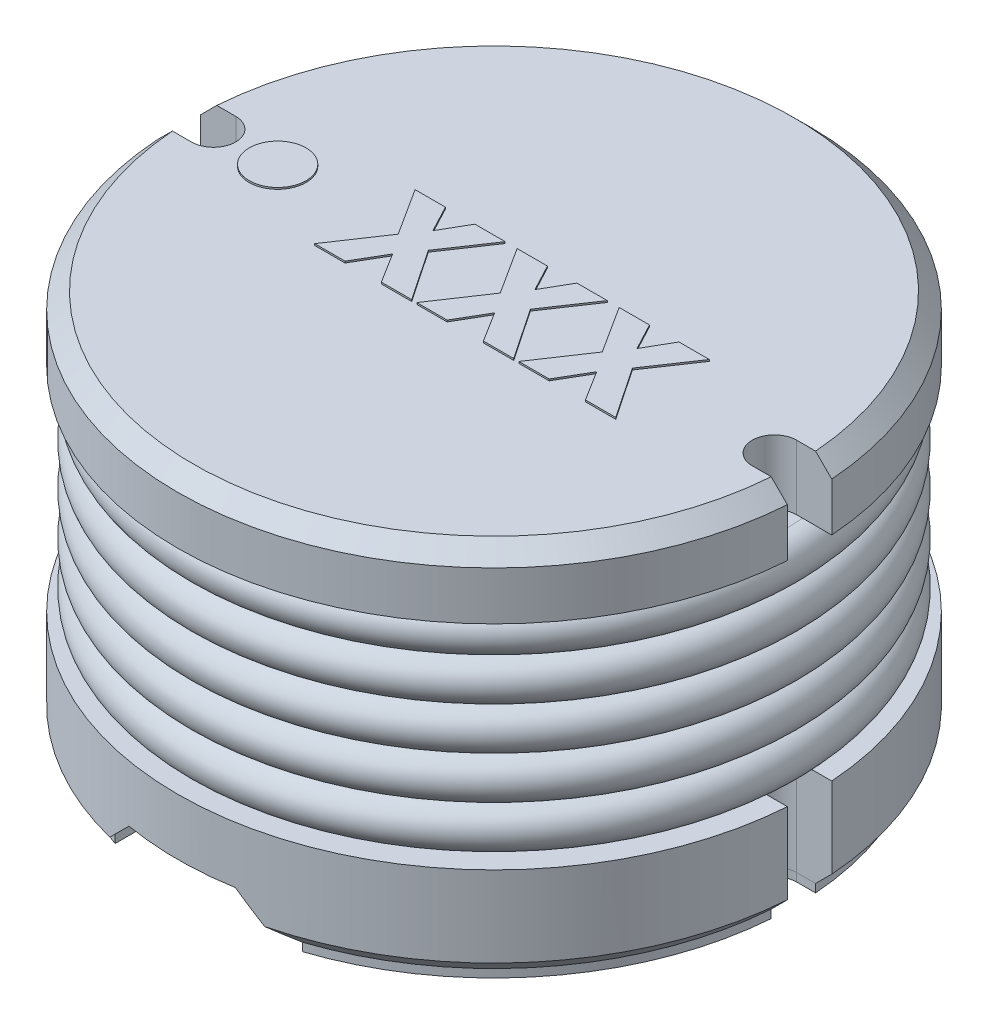
SolidWorks part; units mm, degrees
ref_plane "Front" through (0, 0, 0) normal (0, 0, 1) x (1, 0, 0)
ref_plane "Top" through (0, 0, 0) normal (0, 1, 0) x (1, 0, 0)
ref_plane "Right" through (0, 0, 0) normal (1, 0, 0) x (0, 0, -1)
sketch "Sketch1" plane through (0, 0, 0) normal (0, 0, 1) x (1, 0, 0)
  line L0 (0, -9.0753) -> (0, 11.2417) construction
  line L1 (0, 0) -> (4.65, 0)
  line L2 (4.9, 0.25) -> (4.9, 1.5)
  line L3 (4.9, 1.5) -> (4, 1.5)
  line L4 (4, 1.5) -> (4, 4.8)
  line L5 (4, 4.8) -> (4.9, 4.8)
  line L6 (4.9, 4.8) -> (4.9, 5.55)
  line L7 (4.65, 5.8) -> (0, 5.8)
  line L8 (0, 5.8) -> (0, 0)
  line L9 (4.9, 5.55) -> (4.65, 5.8)
  line L10 (4.65, 0) -> (4.9, 0.25)
  point P4 (4.9, 0)
  point P10 (4.9, 5.8)
  dimension "D1" = 9.8
  dimension "D2" = 5.8
  dimension "D3" = 1
  dimension "D4" = 1.5
  dimension "D5" = 8
revolve "Revolve: Main Core Shape" add sketch "Sketch1" angle 360 about L0
sketch "Sketch2" plane through (0, 0, 0) normal (0, 0, 1) x (1, 0, 0)
  line L0 (-1.45, 0) -> (-0.825, 0.625)
  line L1 (-4.65, 0) -> (4.65, 0) construction
  line L2 (-0.825, 0.625) -> (0.825, 0.625)
  line L3 (0.825, 0.625) -> (1.45, 0)
  line L4 (1.45, 0) -> (-1.45, 0)
  line L5 (0, -1.0768) -> (0, 6.9039) construction
  dimension "D1" = 45
  dimension "D2" = 2.9
  dimension "D3" = 0.625
extrude "CutExtd: Bottom Notch" cut sketch "Sketch2" against normal through all and the other way through all
sketch "Sketch3" plane through (0, 0, 0) normal (0, 1, 0) x (1, 0, 0)
  line L0 (-4.9, 0) -> (4.9, 0) construction
  line L1 (-5.4563, 0) -> (-4.3437, 0) construction
  line L2 (-5.4563, 0.3437) -> (-4.3437, 0.3437)
  line L3 (-5.4563, -0.3437) -> (-4.3437, -0.3437)
  line L4 (5.4563, 0) -> (4.3437, 0) construction
  line L5 (5.4563, -0.3437) -> (4.3437, -0.3437)
  line L6 (5.4563, 0.3437) -> (4.3437, 0.3437)
  circle A0 centre (0, 0) radius 4.9 construction
  arc A1 (-5.4563, 0.3437) -> (-5.4563, -0.3437) centre (-5.4563, 0) ccw
  arc A2 (-4.3437, -0.3437) -> (-4.3437, 0.3437) centre (-4.3437, 0) ccw
  arc A3 (5.4563, -0.3437) -> (5.4563, 0.3437) centre (5.4563, 0) ccw
  arc A4 (4.3437, 0.3437) -> (4.3437, -0.3437) centre (4.3437, 0) ccw
  circle A5 centre (0, 0) radius 4.3437 construction
  circle A8 centre (0, 0) radius 4 construction
  circle A9 centre (0, 0) radius 4 construction
  point P7 (-4.9, 0)
  point P13 (4.9, 0)
extrude "CutExtd: Top/Bot Wire PassThrus" cut sketch "Sketch3" along normal through all
sketch "Sketch4" plane through (0, 0, 0) normal (0, 1, 0) x (1, 0, 0)
  line L1 (-1.45, -4.4181) -> (-1.45, 4.4181)
  line L2 (-4.6373, 0.3437) -> (-4.3437, 0.3437)
  line L3 (-4.3437, -0.3437) -> (-4.6373, -0.3437)
  line L4 (4.6373, 0.3437) -> (4.3437, 0.3437) construction
  line L5 (4.3437, -0.3437) -> (4.6373, -0.3437)
  line L6 (4.6373, 0.3437) -> (4.3437, 0.3437)
  line L7 (1.45, -4.4181) -> (1.45, 4.4181)
  arc A0 (-1.45, -4.4181) -> (-4.6373, -0.3437) centre (0, 0) cw
  arc A1 (-4.6373, 0.3437) -> (-1.45, 4.4181) centre (0, 0) cw
  arc A2 (-4.3437, -0.3437) -> (-4.3437, 0.3437) centre (-4.3437, 0) ccw
  arc A3 (4.3437, 0.3437) -> (4.3437, -0.3437) centre (4.3437, 0) ccw construction
  arc A4 (-4.6373, -0.3437) -> (-1.45, -4.4181) centre (0, 0) ccw construction
  arc A5 (-1.45, 4.4181) -> (-4.6373, 0.3437) centre (0, 0) ccw construction
  arc A6 (-4.3437, -0.3437) -> (-4.3437, 0.3437) centre (-4.3437, 0) ccw construction
  arc A7 (4.3437, -0.3437) -> (4.3437, 0.3437) centre (4.3437, 0) cw
  arc A8 (4.6373, 0.3437) -> (1.45, 4.4181) centre (0, 0) ccw
  arc A9 (1.45, -4.4181) -> (4.6373, -0.3437) centre (0, 0) ccw
  arc A10 (4.6373, 0.3437) -> (1.45, 4.4181) centre (0, 0) ccw construction
extrude "ExtdBoss: Electrodes on Bottom" add sketch "Sketch4" against normal blind 0.127 separate body
sketch "Sketch5" plane through (0, 0, 0) normal (1, 0, 0) x (0, 0, -1)
  line L0 (4, 4.8) -> (4, 1.5)
  line L1 (4, 4.8) -> (4.4494, 4.8)
  line L2 (0.3437, 4.8) -> (4.9, 4.8) construction
  line L3 (4, 1.5) -> (4.4494, 1.5)
  line L4 (4.9, 1.5) -> (0.3437, 1.5) construction
  line L5 (4.4494, 4.8) -> (4.4494, 1.5) construction
  line L6 (4.7794, 1.83) -> (4.7794, 4.47) construction
  line L7 (0, 0) -> (0, 5.8) construction
  line L8 (0.3437, 5.8) -> (-0.3437, 5.8) construction
  arc A0 (4.4494, 4.8) -> (4.4494, 4.14) centre (4.4494, 4.47) cw
  arc A1 (4.4494, 1.5) -> (4.4494, 2.16) centre (4.4494, 1.83) ccw
  arc A2 (4.4494, 2.16) -> (4.4494, 2.82) centre (4.4494, 2.49) ccw
  arc A3 (4.4494, 4.14) -> (4.4494, 3.48) centre (4.4494, 3.81) cw
  arc A4 (4.4494, 3.48) -> (4.4494, 2.82) centre (4.4494, 3.15) cw
revolve "Revolve: Coil" add sketch "Sketch5" angle 360 about L7
sketch "Sketch6" plane through (0, 5.8, 0) normal (0, 1, 0) x (1, 0, 0)
  circle A0 centre (-3.3512, 0) radius 0.4401
  text T0 "xxx" font "Arial" height in points 8
extrude "BossExtd: Label (Top)" add sketch "Sketch6" along normal blind 0.0254 separate body
